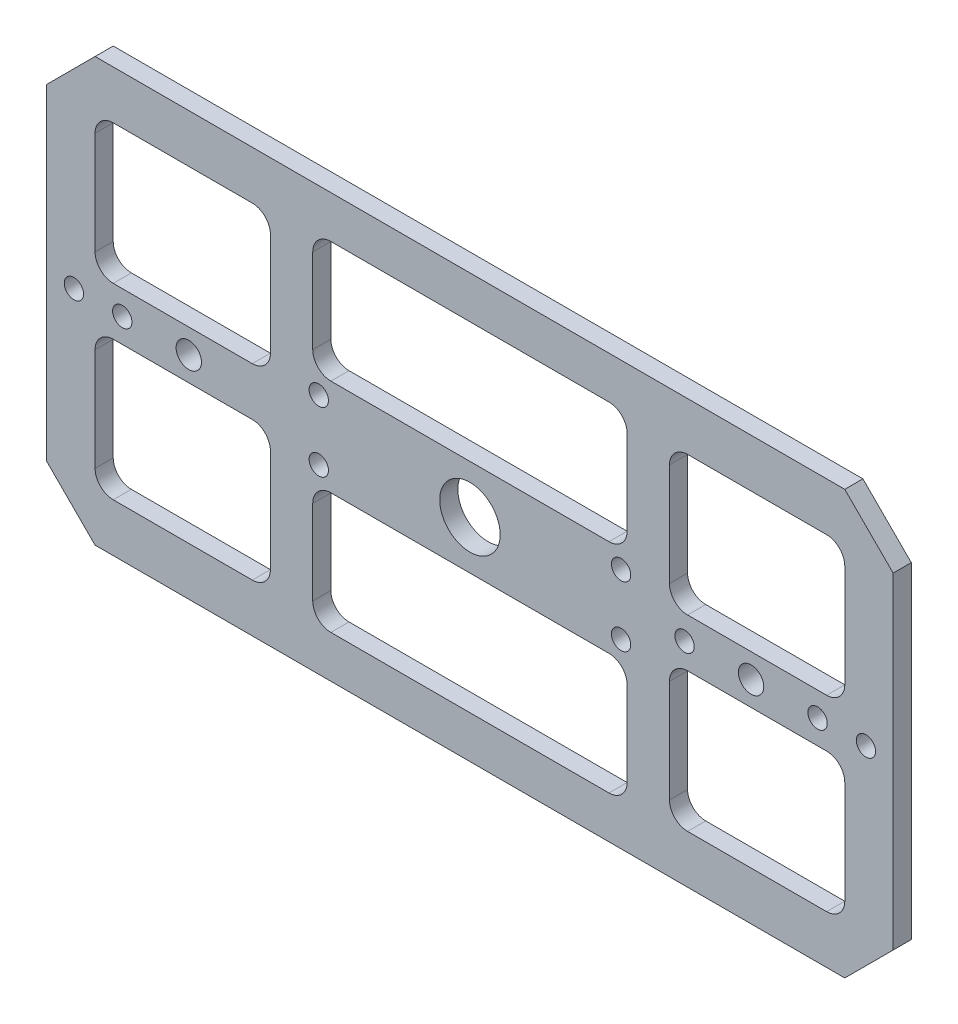
SolidWorks part; units mm, degrees
material "Thornel Mat VMA"
ref_plane "前视基准面" through (0, 0, 0) normal (0, 0, 1) x (1, 0, 0)
ref_plane "上视基准面" through (0, 0, 0) normal (0, 1, 0) x (1, 0, 0)
ref_plane "右视基准面" through (0, 0, 0) normal (1, 0, 0) x (0, 0, -1)
sketch "草图1" plane through (0, 0, 0) normal (0, 0, 1) x (1, 0, 0)
  line L0 (0, 25.9347) -> (0, -32.8628) construction
  line L1 (-58.6564, 0) -> (66.0734, 0) construction
  line L3 (-70, 35) -> (70, 35)
  line L4 (-70, 35) -> (-70, -35)
  line L5 (-70, -35) -> (70, -35)
  line L6 (70, 35) -> (70, -35)
  circle A0 centre (-25, 5) radius 1.6
  circle A1 centre (25, 5) radius 1.6
  circle A2 centre (-25, -5) radius 1.6
  circle A3 centre (25, -5) radius 1.6
  circle A4 centre (0, 0) radius 5
  dimension "D1" = 10
  dimension "D2" = 50
  dimension "D3" = 3.2
  dimension "D7" = 10
  dimension "D4" = 30
  dimension "D5" = 30
  dimension "D6" = 70
extrude "凸台-拉伸1" add sketch "草图1" along normal blind 3
sketch "草图2" plane through (0, 0, 3) normal (0, 0, 1) x (1, 0, 0)
  line L0 (0, 60.8083) -> (0, -64.8579) construction
  line L1 (-70, 0) -> (70, 0) construction
  line L2 (-70, 35) -> (-70, -35) construction
  line L3 (-62, 27) -> (-33, 27)
  line L4 (-62, 27) -> (-62, 4)
  line L5 (-62, 4) -> (-33, 4)
  line L6 (-33, 27) -> (-33, 4)
  line L7 (-62, -4) -> (-33, -4)
  line L8 (-62, -4) -> (-62, -27)
  line L9 (-62, -27) -> (-33, -27)
  line L10 (-33, -4) -> (-33, -27)
  line L11 (70, 35) -> (-70, 35) construction
  line L12 (62, -27) -> (33, -27)
  line L13 (33, -4) -> (33, -27)
  line L14 (62, -4) -> (33, -4)
  line L15 (62, -4) -> (62, -27)
  line L16 (62, 4) -> (33, 4)
  line L17 (33, 27) -> (33, 4)
  line L18 (62, 27) -> (33, 27)
  line L19 (62, 27) -> (62, 4)
  line L20 (70, -35) -> (70, 35) construction
  line L21 (-70, -35) -> (70, -35) construction
  line L22 (-26, 28) -> (26, 28)
  line L23 (-26, 28) -> (-26, 8)
  line L24 (-26, 8) -> (26, 8)
  line L25 (26, 28) -> (26, 8)
  line L26 (-26, 28) -> (26, 8) construction
  line L27 (-26, 8) -> (26, 28) construction
  line L28 (-26, -8) -> (26, -8)
  line L29 (-26, -8) -> (-26, -28)
  line L30 (-26, -28) -> (26, -28)
  line L31 (26, -8) -> (26, -28)
  line L32 (-26, -8) -> (26, -28) construction
  line L33 (-26, -28) -> (26, -8) construction
  circle A0 centre (-25, 5) radius 1.6 construction
  circle A1 centre (25, -5) radius 1.6 construction
  circle A2 centre (25, 5) radius 1.6 construction
  point P13 (0, 18)
  point P34 (0, -18)
  dimension "D1" = 8
  dimension "D2" = 8
  dimension "D3" = 8
  dimension "D4" = 8
  dimension "D5" = 3
  dimension "D6" = 7
  dimension "D7" = 7
  dimension "D8" = 3
  dimension "D9" = 7
extrude "切除-拉伸1" cut sketch "草图2" against normal through all
fillet "圆角1" radius 3 24 edges at (-33, -27, 1.5) (-62, -27, 1.5) (-62, -4, 1.5) (-33, -4, 1.5) (-33, 4, 1.5) (-62, 4, 1.5) (-62, 27, 1.5) (-33, 27, 1.5) (33, 4, 1.5) (33, 27, 1.5) (62, 27, 1.5) (62, 4, 1.5) (62, -27, 1.5) (62, -4, 1.5) (33, -4, 1.5) (33, -27, 1.5) (26, -28, 1.5) (26, -8, 1.5) (-26, -28, 1.5) (-26, -8, 1.5) (26, 28, 1.5) (26, 8, 1.5) (-26, 8, 1.5) (-26, 28, 1.5)
chamfer "倒角1" distance 8 angle 45 4 edges at (70, 35, 1.5) (70, -35, 1.5) (-70, -35, 1.5) (-70, 35, 1.5)
sketch "草图3" plane through (0, 0, 3) normal (0, 0, 1) x (1, 0, 0)
  line L0 (0, 45.9211) -> (0, -39.3483) construction
  line L1 (-79.4071, 0) -> (79.2295, 0) construction
  line L2 (-46.5, 5.8613) -> (-46.5, 0) construction
  circle A0 centre (-46.5, 0) radius 2.1
  circle A1 centre (46.5, 0) radius 2.1
  circle A2 centre (-57.5, 0) radius 1.6
  circle A3 centre (-35.5, 0) radius 1.6 construction
  circle A4 centre (57.5, 0) radius 1.6
  circle A5 centre (35.5, 0) radius 1.6
  circle A6 centre (-65.5, 0) radius 1.6
  circle A7 centre (65.5, 0) radius 1.6
  dimension "D1" = 4.2
  dimension "D2" = 93
  dimension "D3" = 22
  dimension "D4" = 3.2
  dimension "D5" = 8
extrude "切除-拉伸2" cut sketch "草图3" against normal through all
